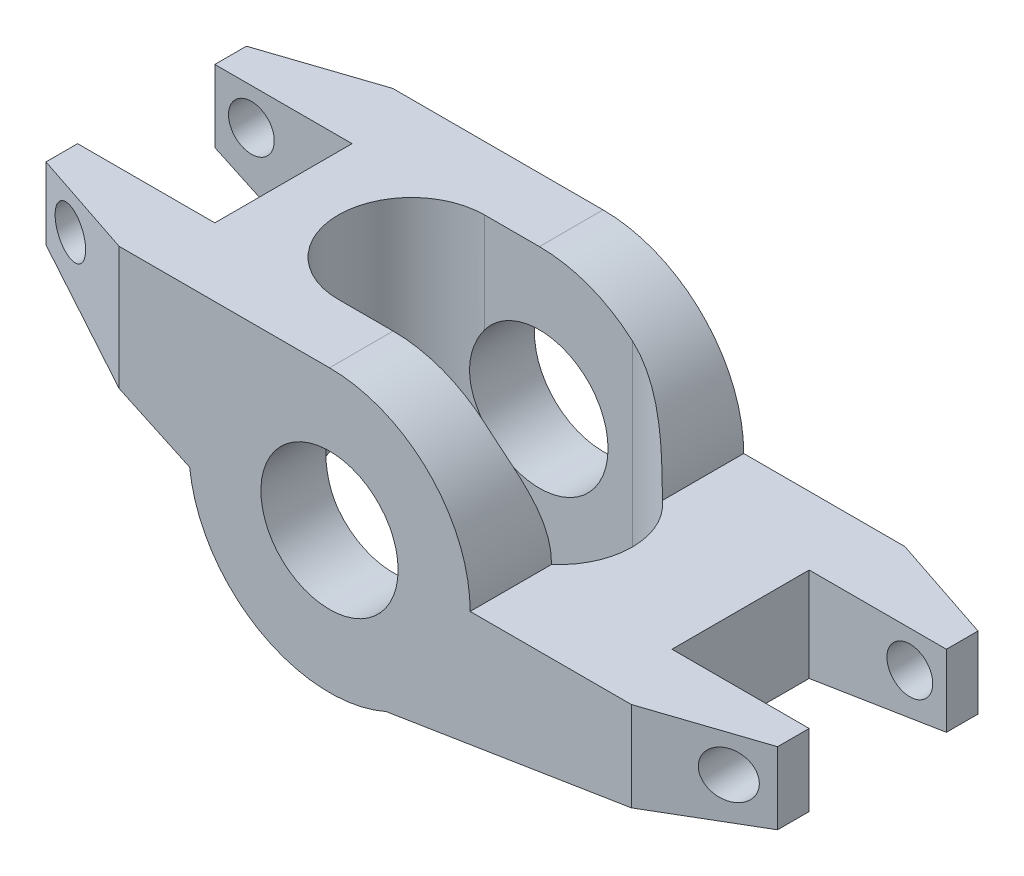
SolidWorks part; units mm, degrees
ref_plane "Front Plane" through (0, 0, 0) normal (0, 0, 1) x (1, 0, 0)
ref_plane "Top Plane" through (0, 0, 0) normal (0, 1, 0) x (1, 0, 0)
ref_plane "Right Plane" through (0, 0, 0) normal (1, 0, 0) x (0, 0, -1)
sketch "Sketch1" plane through (0, 0, 0) normal (0, 0, 1) x (1, 0, 0)
  line L0 (0, 9.77) -> (-22.23, 9.77)
  line L1 (-22.23, 9.77) -> (-22.23, 4.77)
  line L2 (-22.23, 4.77) -> (-9.7115, -1.0675)
  line L3 (9.77, 0) -> (28.58, 0)
  line L4 (28.58, 0) -> (28.58, -5)
  line L5 (28.58, -5) -> (3.9342, -8.9429)
  arc A0 (-9.7115, -1.0675) -> (3.9342, -8.9429) centre (0, 0) ccw
  circle A1 centre (0, 0) radius 4.765
  arc A2 (9.77, 0) -> (0, 9.77) centre (0, 0) ccw
  dimension "D1" = 19.54
  dimension "D2" = 9.53
  dimension "D3" = 5
  dimension "D4" = 22.23
  dimension "D5" = 25
  dimension "D6" = 28.58
extrude "Boss-Extrude1" add sketch "Sketch1" along normal mid plane 19
chamfer "Chamfer1" distance 7.62 distance2 2.54 2 edges at (28.58, -2.5, -9.5) (-22.23, 7.27, -9.5)
chamfer "Chamfer2" distance 2.54 distance2 7.62 2 edges at (28.58, -2.5, 9.5) (-22.23, 7.27, 9.5)
sketch "Sketch2" plane through (0, 9.77, 0) normal (0, 1, 0) x (1, 0, 0)
  line L0 (-22.23, -6.96) -> (-22.23, 6.96) construction
  line L1 (-22.23, 4.765) -> (-12.7, 4.765)
  line L2 (-22.23, 4.765) -> (-22.23, -4.765)
  line L3 (-22.23, -4.765) -> (-12.7, -4.765)
  line L4 (-12.7, 4.765) -> (-12.7, -4.765)
  line L5 (28.58, -6.96) -> (28.58, 6.96) construction
  line L10 (28.58, 4.765) -> (19.05, 4.765)
  line L11 (28.58, 4.765) -> (28.58, -4.765)
  line L12 (28.58, -4.765) -> (19.05, -4.765)
  line L13 (19.05, 4.765) -> (19.05, -4.765)
  point P12 (-12.7, 0)
  point P13 (19.05, 0)
  dimension "D1" = 9.53
extrude "Cut-Extrude1" cut sketch "Sketch2" against normal through all
sketch "Sketch3" plane through (0, 0, 0) normal (0, 1, 0) x (1, 0, 0)
  line L0 (-3.81, 0) -> (6.45, 0) construction
  line L1 (-3.81, 5.08) -> (6.45, 5.08)
  line L2 (-3.81, -5.08) -> (6.45, -5.08)
  line L3 (-12.7, -4.765) -> (-12.7, 4.765) construction
  arc A0 (-3.81, 5.08) -> (-3.81, -5.08) centre (-3.81, 0) ccw
  arc A1 (6.45, -5.08) -> (6.45, 5.08) centre (6.45, 0) ccw
  point P3 (1.32, 0)
  dimension "D2" = 5.08
  dimension "D1" = 8.89
  dimension "D3" = 10.26
extrude "Cut-Extrude2" cut sketch "Sketch3" against normal through all both and the other way through all
sketch "Sketch4" plane through (0, 0, 0) normal (0, 0, 1) x (1, 0, 0)
  line L0 (-22.23, 9.77) -> (-14.61, 9.77) construction
  line L1 (-22.23, 4.77) -> (-22.23, 9.77) construction
  line L2 (28.58, 0) -> (28.58, -5) construction
  line L4 (20.96, 0) -> (28.58, 0) construction
  circle A0 centre (-19.69, 7.23) radius 1.59
  circle A1 centre (26.04, -2.54) radius 1.59
  point P10 (0, 0)
  point P12 (26.7613, 0)
  dimension "D1" = 3.18
  dimension "D2" = 2.54
  dimension "D3" = 2.54
  dimension "D4" = 2.54
  dimension "D5" = 2.54
extrude "Cut-Extrude3" cut sketch "Sketch4" against normal through all both and the other way through all
